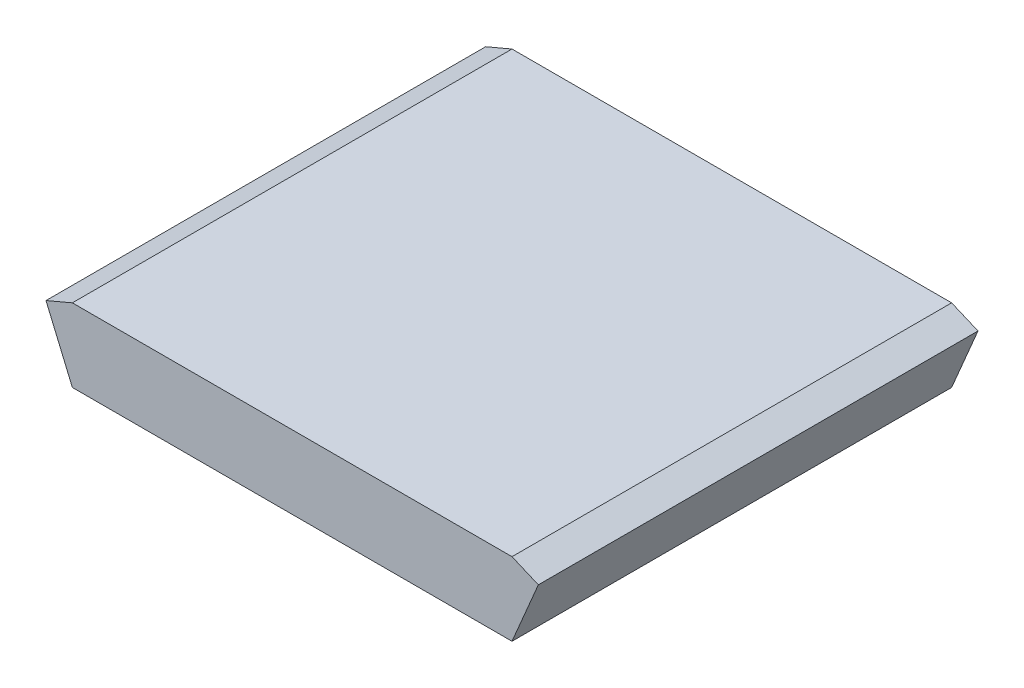
SolidWorks part; units mm, degrees
ref_plane "Front Plane" through (0, 0, 0) normal (0, 0, 1) x (1, 0, 0)
ref_plane "Top Plane" through (0, 0, 0) normal (0, 1, 0) x (1, 0, 0)
ref_plane "Right Plane" through (0, 0, 0) normal (1, 0, 0) x (0, 0, -1)
sketch "Sketch2" plane through (0, 0, 0) normal (0, 0, 1) x (1, 0, 0)
  line L0 (-1.5, -0.25) -> (-1.6798, 0.1737)
  line L1 (-1.5, -0.25) -> (1.5, -0.25)
  line L2 (-1.5, -0.25) -> (-1.5, 0.25)
  line L3 (-1.5, 0.25) -> (1.5, 0.25)
  line L4 (1.5, -0.25) -> (1.5, 0.25)
  line L5 (-1.5, -0.25) -> (1.5, 0.25) construction
  line L6 (-1.5, 0.25) -> (1.5, -0.25) construction
  line L7 (-1.6798, 0.1737) -> (-1.5, 0.25)
  line L8 (0, 0.25) -> (0, -0.25) construction
  line L9 (1.6798, 0.1737) -> (1.5, 0.25)
  line L10 (1.5, -0.25) -> (1.6798, 0.1737)
  point P0 (0, 0)
  dimension "D1" = 3
  dimension "D2" = 0.5
  dimension "D3" = 67
  dimension "D4" = 90
extrude "Boss-Extrude1" add sketch "Sketch2" along normal blind 1.5 and the other way blind 1.5 contours L7 L0 L2 | L1 L4 L3 L2 | L4 L10 L9
